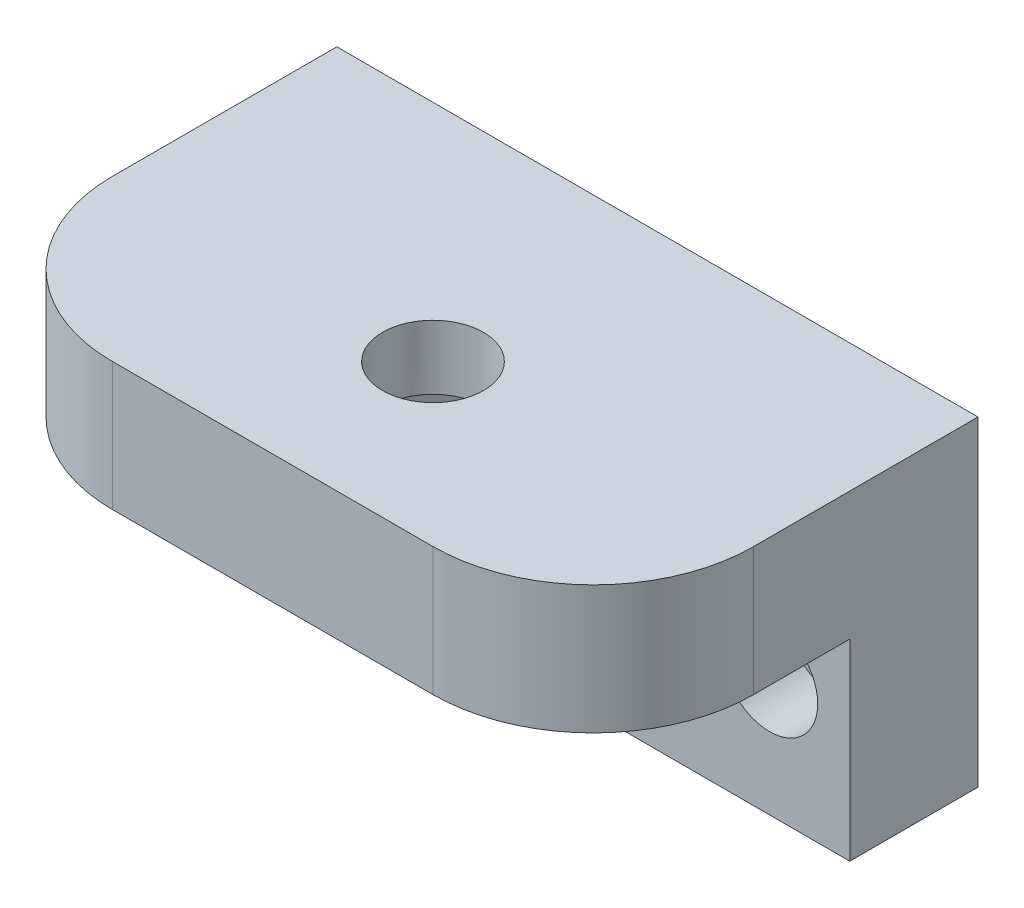
SolidWorks part; units mm, degrees
ref_plane "Front Plane" through (0, 0, 0) normal (0, 0, 1) x (1, 0, 0)
ref_plane "Top Plane" through (0, 0, 0) normal (0, 1, 0) x (1, 0, 0)
ref_plane "Right Plane" through (0, 0, 0) normal (1, 0, 0) x (0, 0, -1)
sketch "Sketch1" plane through (0, 0, 0) normal (0, 0, 1) x (1, 0, 0)
  line L1 (-20, -10) -> (20, -10)
  line L2 (-20, -10) -> (-20, 10)
  line L3 (-20, 10) -> (20, 10)
  line L4 (20, -10) -> (20, 10)
  line L5 (-20, -10) -> (20, 10) construction
  line L6 (-20, 10) -> (20, -10) construction
  point P0 (0, 0)
  dimension "D1" = 40
  dimension "D2" = 20
extrude "Boss-Extrude1" add sketch "Sketch1" along normal blind 8
sketch "Sketch2" plane through (0, 0, 8) normal (0, 0, 1) x (1, 0, 0)
  line L0 (20, -10) -> (20, 10) construction
  line L1 (-20, 10) -> (20, 10)
  line L2 (-20, 10) -> (-20, 2)
  line L3 (-20, 2) -> (20, 2)
  line L4 (20, 10) -> (20, 2)
  dimension "D1" = 8
extrude "Boss-Extrude2" add sketch "Sketch2" along normal blind 16
sketch "Sketch4" plane through (0, 10, 0) normal (0, 1, 0) x (1, 0, 0)
  line L3 (0, -24) -> (0, -14) construction
  line L6 (20, -24) -> (-20, -24) construction
  circle A1 centre (0, -14) radius 3.15
  dimension "D1" = 6.3
  dimension "D2" = 10
extrude "Cut-Extrude1" cut sketch "Sketch4" against normal through all
sketch "Sketch5" plane through (0, 0, 0) normal (0, 0, -1) x (-1, 0, 0)
  line L0 (-20, -10) -> (-15, -10) construction
  line L1 (20, -10) -> (-20, -10) construction
  line L2 (-15, -10) -> (-15, -2.5) construction
  circle A0 centre (-15, -2.5) radius 1.6
  dimension "D1" = 7.5
  dimension "D2" = 3.2
  dimension "D3" = 5
extrude "Cut-Extrude2" cut sketch "Sketch5" against normal blind 8 contours A0
sketch "Sketch6" plane through (0, 0, 0) normal (0, 0, -1) x (-1, 0, 0)
  line L0 (20, -10) -> (15, -10) construction
  line L1 (20, -10) -> (-20, -10) construction
  line L2 (15, -10) -> (15, -2.5) construction
  circle A0 centre (15, -2.5) radius 1.6
  dimension "D1" = 7.5
  dimension "D3" = 3.2
  dimension "D2" = 5
extrude "Cut-Extrude3" cut sketch "Sketch6" against normal blind 8 contours A0
sketch "Sketch7" plane through (0, 0, 0) normal (0, 0, -1) x (-1, 0, 0)
  line L0 (-20, -10) -> (-11, -10) construction
  line L1 (20, -10) -> (-20, -10) construction
  line L2 (-11, -10) -> (-11, 2.5)
  line L3 (-11, 2.5) -> (-7.5, 2.5)
  line L4 (-7.5, 2.5) -> (-7.5, 6.5)
  line L5 (-7.5, 6.5) -> (7.5, 6.5)
  line L6 (7.5, 6.5) -> (7.5, 2.5)
  line L7 (7.5, 2.5) -> (11, 2.5)
  line L8 (11, 2.5) -> (11, -10)
extrude "Cut-Extrude4" cut sketch "Sketch7" against normal blind 1.6 and the other way through all flip side to cut contours L2 L3 L4 L5 L6 L7 L8
sketch "Sketch9" plane through (0, 0, 8) normal (0, 0, 1) x (1, 0, 0)
  line L0 (-20, -10) -> (-15, -10) construction
  line L1 (-20, -10) -> (20, -10) construction
  line L2 (-15, -10) -> (-15, -2.5) construction
  circle A0 centre (-15, -2.5) radius 3
  dimension "D1" = 6
extrude "Cut-Extrude5" cut sketch "Sketch9" against normal blind 4
sketch "Sketch10" plane through (0, 0, 8) normal (0, 0, 1) x (1, 0, 0)
  line L0 (20, -10) -> (15, -10) construction
  line L1 (20, -10) -> (11, -10) construction
  line L2 (15, -10) -> (15, -2.5) construction
  circle A0 centre (15, -2.5) radius 3
  dimension "D1" = 6
extrude "Cut-Extrude6" cut sketch "Sketch10" against normal blind 4 contours A0
sketch "Sketch11" plane through (0, 2, 0) normal (0, -1, 0) x (1, 0, 0)
  line L1 (6.0622, 14) -> (3.0311, 19.25)
  line L2 (3.0311, 19.25) -> (-3.0311, 19.25)
  line L3 (-3.0311, 19.25) -> (-6.0622, 14)
  line L4 (-6.0622, 14) -> (-3.0311, 8.75)
  line L5 (-3.0311, 8.75) -> (3.0311, 8.75)
  line L6 (3.0311, 8.75) -> (6.0622, 14)
  circle A0 centre (0, 14) radius 5.25 construction
  dimension "D1" = 10.5
extrude "Cut-Extrude7" cut sketch "Sketch11" against normal blind 4
fillet "Fillet1" radius 10 2 edges at (20, 6, 24) (-20, 6, 24)
